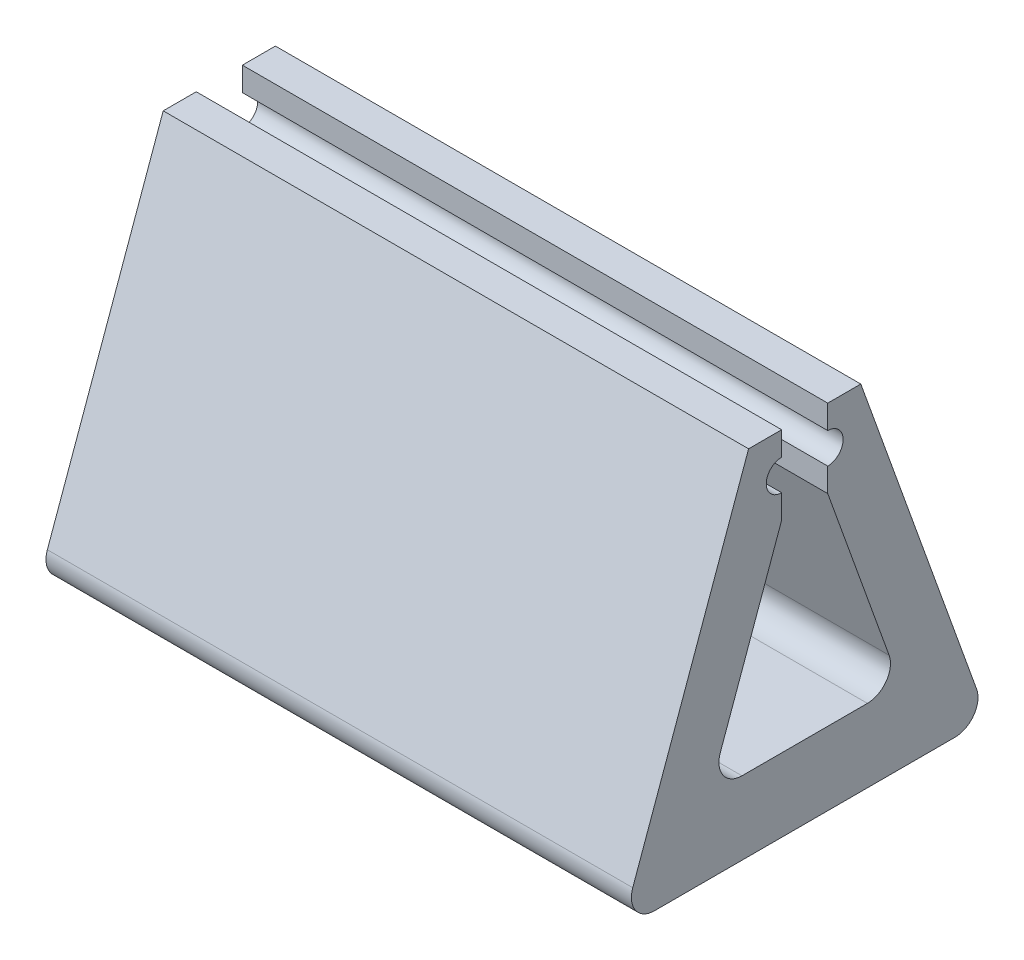
SolidWorks part; units mm, degrees
ref_plane "Front Plane" through (0, 0, 0) normal (0, 0, 1) x (1, 0, 0)
ref_plane "Top Plane" through (0, 0, 0) normal (0, 1, 0) x (1, 0, 0)
ref_plane "Right Plane" through (0, 0, 0) normal (1, 0, 0) x (0, 0, -1)
sketch "Sketch1" plane through (0, 0, 0) normal (1, 0, 0) x (0, 0, -1)
  line L0 (-0.6, 7.2859) -> (-0.6, 5.2461)
  line L1 (-1.633, 0) -> (1.633, 0)
  line L2 (0.6, 5.2461) -> (2.1976, 0.803)
  line L3 (0.6, 7.2859) -> (1.4606, 7.2859)
  line L4 (1.4606, 7.2859) -> (4.4766, -1.1018)
  line L5 (3.912, -1.9048) -> (-3.912, -1.9048)
  line L6 (-4.4766, -1.1018) -> (-1.4606, 7.2859)
  line L7 (-1.4606, 7.2859) -> (-0.6, 7.2859)
  line L8 (0, 0) -> (0, 50000) construction
  line L9 (-0.6, 5.2461) -> (-2.1976, 0.803)
  line L10 (0.6, 7.2859) -> (0.6, 5.2461)
  arc A0 (-2.1976, 0.803) -> (-1.633, 0) centre (-1.633, 0.6) ccw
  arc A1 (1.633, 0) -> (2.1976, 0.803) centre (1.633, 0.6) ccw
  arc A2 (-3.912, -1.9048) -> (-4.4766, -1.1018) centre (-3.912, -1.3048) cw
  arc A3 (3.912, -1.9048) -> (4.4766, -1.1018) centre (3.912, -1.3048) ccw
  arc A4 (-0.6, 5.866) -> (-0.6, 6.666) centre (-0.6, 6.266) cw
  arc A5 (0.6, 5.866) -> (0.6, 6.666) centre (0.6, 6.266) ccw
  point P26 (0, -1.9048)
  dimension "D2" = 0.6
  dimension "D4" = 0.6
  dimension "D6" = 0.4
  dimension "D1" = 1.2
  dimension "D7" = 1.5
extrude "Boss-Extrude1" add sketch "Sketch1" along normal blind 15.24
